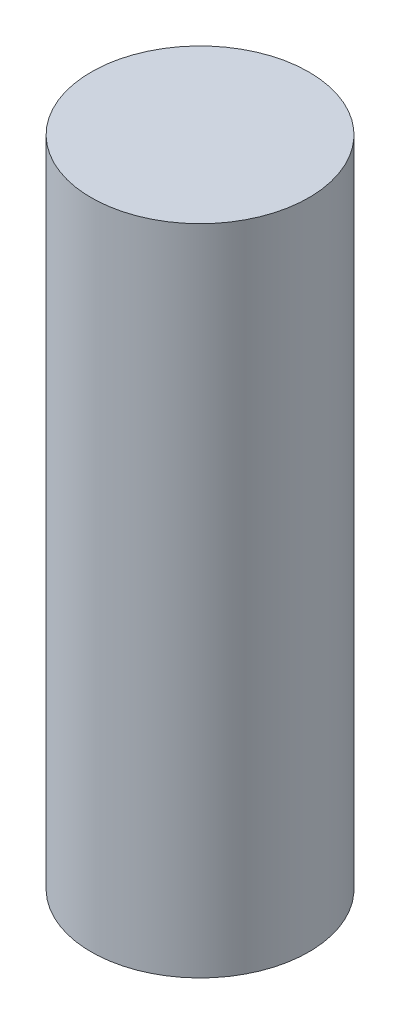
SolidWorks part; units mm, degrees
material "AISI 316 Stainless Steel Sheet (SS)"
ref_plane "Front Plane" through (0, 0, 0) normal (0, 0, 1) x (1, 0, 0)
ref_plane "Top Plane" through (0, 0, 0) normal (0, 1, 0) x (1, 0, 0)
ref_plane "Right Plane" through (0, 0, 0) normal (1, 0, 0) x (0, 0, -1)
sketch "Sketch1" plane through (0, 0, 0) normal (0, 1, 0) x (1, 0, 0)
  circle A0 centre (0, 0) radius 1.5875
extrude "Boss-Extrude1" add sketch "Sketch1" along normal blind 9.525
